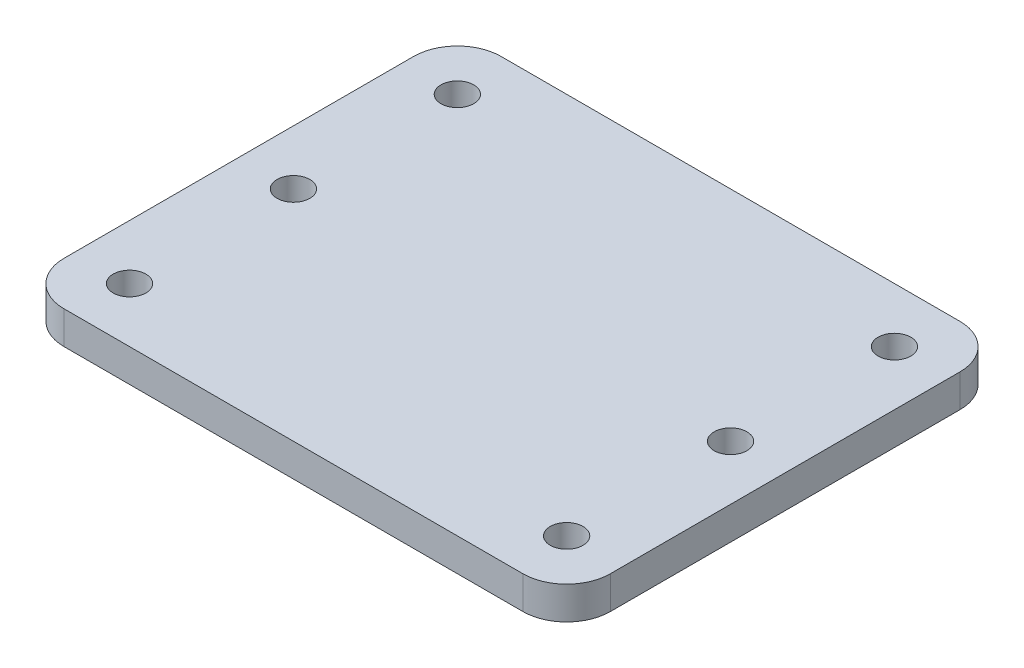
SolidWorks part; units mm, degrees
ref_plane "Front Plane" through (0, 0, 0) normal (0, 0, 1) x (1, 0, 0)
ref_plane "Top Plane" through (0, 0, 0) normal (0, 1, 0) x (1, 0, 0)
ref_plane "Right Plane" through (0, 0, 0) normal (1, 0, 0) x (0, 0, -1)
sketch "Sketch1" plane through (0, 0, 0) normal (0, 1, 0) x (1, 0, 0)
  line L1 (-25, 20) -> (25, 20)
  line L2 (-25, 20) -> (-25, -20)
  line L3 (-25, -20) -> (25, -20)
  line L4 (25, 20) -> (25, -20)
  line L5 (-25, 20) -> (25, -20) construction
  line L6 (-25, -20) -> (25, 20) construction
  point P0 (0, 0)
  dimension "D1" = 50
  dimension "D2" = 40
extrude "Boss-Extrude1" add sketch "Sketch1" along normal blind 3
fillet "Fillet1" radius 4 4 edges at (25, 1.5, 20) (25, 1.5, -20) (-25, 1.5, -20) (-25, 1.5, 20)
sketch "Sketch2" plane through (0, 0, 0) normal (0, 1, 0) x (1, 0, 0)
  circle A0 centre (-20, 0) radius 1.5
  circle A1 centre (20, 0) radius 1.5
  point P4 (0, 0)
  dimension "D1" = 3
  dimension "D2" = 3
  dimension "D3" = 20
  dimension "D4" = 20
extrude "Cut-Extrude1" cut sketch "Sketch2" along normal blind 3
sketch "Sketch3" plane through (0, 0, 0) normal (0, 1, 0) x (1, 0, 0)
  circle A0 centre (-20, -15) radius 1.5
  circle A1 centre (20, -15) radius 1.5
  circle A2 centre (20, 15) radius 1.5
  circle A3 centre (-20, 15) radius 1.5
  point P8 (0, 0)
  point P9 (0, 0)
  point P11 (0, 0)
  dimension "D1" = 3
  dimension "D2" = 3
  dimension "D3" = 3
  dimension "D4" = 3
  dimension "D5" = 40
  dimension "D6" = 40
  dimension "D7" = 30
  dimension "D8" = 20
  dimension "D9" = 15
extrude "Cut-Extrude3" cut sketch "Sketch3" along normal blind 3
